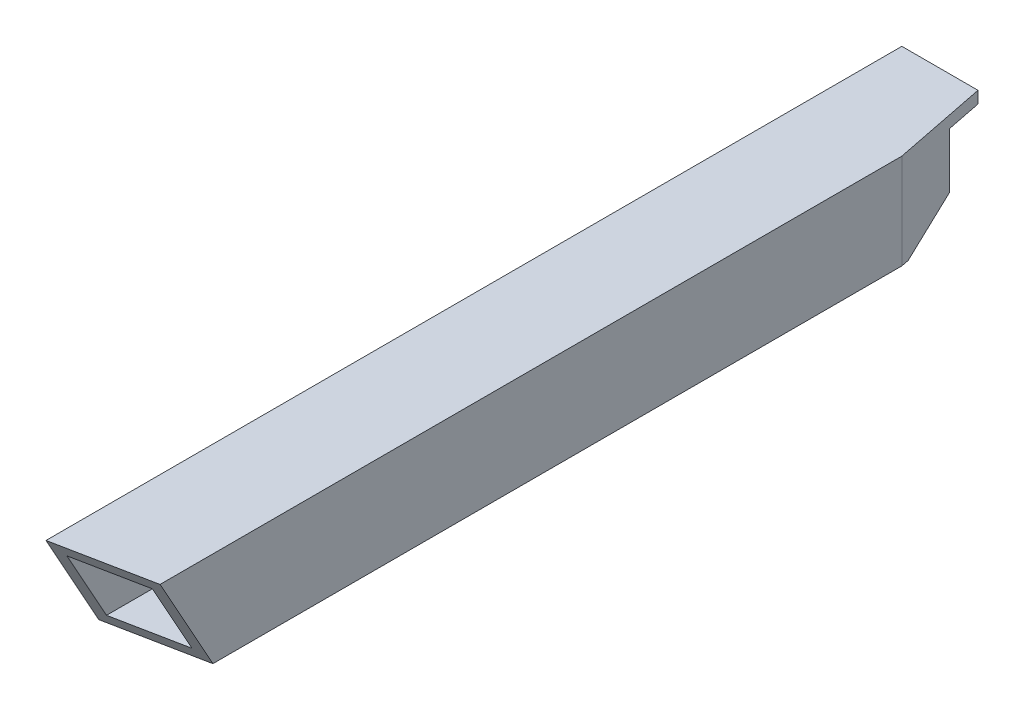
SolidWorks part; units mm, degrees
material "6061 Alloy"
ref_plane "Front Plane" through (0, 0, 0) normal (0, 0, 1) x (1, 0, 0)
ref_plane "Top Plane" through (0, 0, 0) normal (0, 1, 0) x (1, 0, 0)
ref_plane "Right Plane" through (0, 0, 0) normal (1, 0, 0) x (0, 0, -1)
sketch "Sketch1" plane through (0, 0, 0) normal (0, 0, 1) x (1, 0, 0)
  line L0 (12.7, 0) -> (9.525, 0) construction
  line L1 (-12.7, 0) -> (12.7, 0) construction
  line L2 (0, 12.7) -> (0, -12.7)
  point P7 (0, 0)
sketch "Sketch2" plane through (0, 0, 0) normal (1, 0, 0) x (0, 0, -1)
  line L0 (114.3, 0) -> (-114.3, 0)
  point P4 (0, 0)
  dimension "Length" = 228.6
sketch "Sketch3" plane through (0, 0, 0) normal (0, 0, 1) x (1, 0, 0)
  line L0 (-12.7, 0) -> (12.7, 0) construction
  line L5 (12.7, -12.7) -> (-12.7, -12.7)
  line L6 (12.7, -12.7) -> (12.7, 12.7)
  line L11 (12.7, 12.7) -> (-12.7, 12.7)
  line L12 (-12.7, -12.7) -> (-12.7, 12.7)
  line L14 (12.7, -12.7) -> (-12.7, 12.7) construction
  line L15 (12.7, 12.7) -> (-12.7, -12.7) construction
  line L16 (9.525, -9.525) -> (-9.525, -9.525)
  line L17 (9.525, -9.525) -> (9.525, 9.525)
  line L18 (9.525, 9.525) -> (-9.525, 9.525)
  line L19 (-9.525, -9.525) -> (-9.525, 9.525)
  line L20 (9.525, -9.525) -> (-9.525, 9.525) construction
  line L21 (9.525, 9.525) -> (-9.525, -9.525) construction
  point P0 (0, 0)
  point P5 (0, 0)
  point P13 (9.525, -12.7)
  dimension "D1" = 3.175
  dimension "D3" = 25.4
  dimension "D4" = 25.4
extrude "Boss-Extrude1" add sketch "Sketch3" along normal up to vertex (114.3 mm away) and the other way up to vertex (114.3 mm away) up to point (0, 0, 114.3) other way up to point (0, 0, -114.3)
sketch "Sketch5" plane through (0, 0, 0) normal (1, 0, 0) x (0, 0, -1)
  line L0 (-114.3, 0) -> (114.3, 0) construction
  line L3 (-114.3, -12.7) -> (-114.3, 12.7) construction
  line L4 (114.3, -12.7) -> (114.3, 12.7) construction
  point P6 (-85.725, 0)
  point P7 (-76.2, 0)
  point P8 (76.2, 0)
  point P10 (85.725, 0)
  dimension "D1" = 28.575
  dimension "D2" = 38.1
  dimension "D3" = 28.575
  dimension "D4" = 38.1
sketch "Sketch7" plane through (0, 12.7, 0) normal (0, -1, 0) x (1, 0, 0)
  line L0 (-12.7, 114.3) -> (12.7, 109.243) construction
  line L1 (12.7, 114.3) -> (12.7, -114.3) construction
  line L2 (-12.7, 114.3) -> (12.7, 114.3) construction
  dimension "D1" = 11.26
ref_plane "Plane2" through (21.4046, 0, 107.51) normal (0.1953, 0, 0.9808) x (0, -1, 0)
ref_plane "Plane3" through (15.4542, -43.1698, 77.6227) normal (0.1714, -0.4788, 0.861) x (0.9808, 0, -0.1953)
other "SurfaceCut2"
sketch "Sketch8" plane through (0, -12.7, 0) normal (0, -1, 0) x (1, 0, 0)
  line L0 (12.7, -88.9) -> (7.643, -114.3) construction
  line L1 (12.7, 95.1168) -> (12.7, -114.3) construction
  line L2 (-12.7, -114.3) -> (12.7, -114.3) construction
  dimension "D1" = 11.26
  dimension "D2" = 25.4
sketch "Sketch10" plane through (-12.7, 0, 0) normal (-1, 0, 0) x (0, 0, 1)
  line L0 (-88.9, -12.7) -> (-114.3, -0.4885) construction
  line L1 (100.0375, -12.7) -> (-114.3, -12.7) construction
  line L2 (-114.3, 12.7) -> (-114.3, -12.7) construction
  dimension "D1" = 25.677
  dimension "D2" = 25.4
sketch "Sketch9" plane through (0, 0, -114.3) normal (0, 0, -1) x (-1, 0, 0)
  line L0 (-7.643, -12.7) -> (-7.643, 12.7) construction
  line L1 (-12.7, 12.7) -> (12.7, 12.7) construction
  line L2 (12.7, -0.4885) -> (-12.7, 0) construction
  line L3 (-12.7, -12.7) -> (-12.7, 12.7) construction
ref_plane "Plane4" through (29.2404, 0, -5.8216) normal (0.9808, 0, -0.1953) x (0, 1, 0)
other "SurfaceCut4"
ref_plane "Plane5" through (0.9271, -48.2076, -26.2782) normal (0.0169, -0.8779, -0.4785) x (0.9998, 0.0192, 0)
other "SurfaceCut6"
equation "\"D1@Sketch3\"=\"Wall thickness@Sketch1\""
equation "\"D1@Sketch5\"=\"Width@Sketch1\"*1.125"
equation "\"D2@Sketch5\"=\"Width@Sketch1\"*1.5"
equation "\"D3@Sketch5\"=\"D1@Sketch5\""
equation "\"D4@Sketch5\"=\"D2@Sketch5\""
equation "\"D2@Sketch3\"=\"Wall Thickness@Sketch1\""
